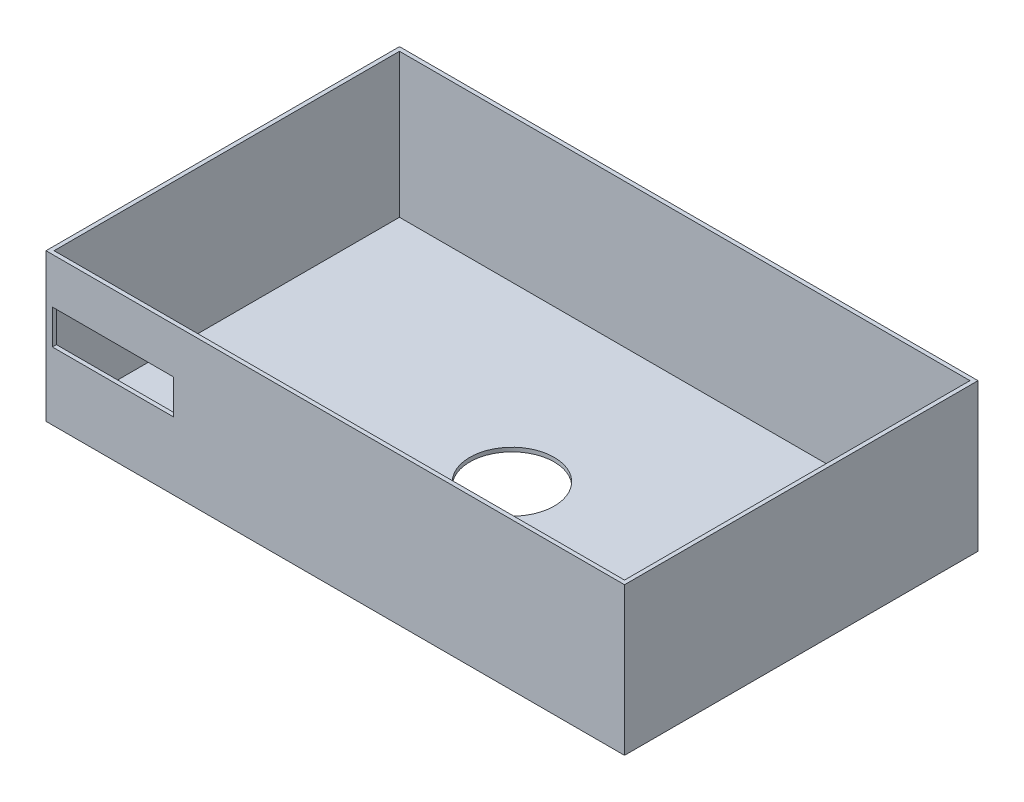
SolidWorks part; units mm, degrees
ref_plane "Front Plane" through (0, 0, 0) normal (0, 0, 1) x (1, 0, 0)
ref_plane "Top Plane" through (0, 0, 0) normal (0, 1, 0) x (1, 0, 0)
ref_plane "Right Plane" through (0, 0, 0) normal (1, 0, 0) x (0, 0, -1)
sketch "Sketch1" plane through (0, 0, 0) normal (0, 1, 0) x (1, 0, 0)
  line L1 (0, 0) -> (1370, 0)
  line L2 (0, 0) -> (0, 837.05)
  line L3 (0, 837.05) -> (1370, 837.05)
  line L4 (1370, 0) -> (1370, 837.05)
  dimension "D1" = 1370
  dimension "D2" = 837.05
extrude "Boss-Extrude1" add sketch "Sketch1" along normal blind 350
shell "Shell1" thickness 9.525
sketch "Sketch3" plane through (0, 0, 0) normal (0, 0, 1) x (1, 0, 0)
  line L1 (15, 242.1) -> (302.4, 242.1)
  line L3 (15, 160.1) -> (302.4, 160.1)
  line L4 (302.4, 242.1) -> (302.4, 160.1)
  line L6 (15, 242.1) -> (15, 160.1)
  line L7 (0, 0) -> (1370, 0) construction
  line L8 (0, 350) -> (0, 0) construction
  dimension "D1" = 82
  dimension "D2" = 160.1
  dimension "D3" = 15
  dimension "D4" = 287.4
extrude "Cut-Extrude1" cut sketch "Sketch3" against normal up to surface (9.525 mm away) up to face at (685, 179.7625, -9.525)
sketch "Sketch7" plane through (0, 0, 0) normal (0, -1, 0) x (1, 0, 0)
  line L0 (685, 0) -> (685, -837.05) construction
  line L1 (0, 0) -> (1370, 0) construction
  line L2 (1370, -837.05) -> (0, -837.05) construction
  circle A0 centre (685, -418.525) radius 100
  dimension "D1" = 200
extrude "Cut-Extrude2" cut sketch "Sketch7" against normal up to next
equation "\"No. Of Teeth\"= 25"
equation "\"Module\"= 1.5"
equation "\"Bore Diameter\"= 10"
equation "\"Pressure Angle\"= 20"
equation "\"Outer Diameter\"= ( \"No. Of Teeth\" + 2 ) * ( \"Module\" )"
equation "\"Pitch diameter\"= \"No. Of Teeth\" * \"Module\""
equation "\"Backlash\"= 0.3 * \"Module\""
equation "\"Arc Length\"= ( ( \"Module\" * pi ) / 2 ) + \"Backlash\""
equation "\"Fillet Radius\"= 0.38 * \"Module\""
equation "\"Tooth Depth\"= IIF ( \"Module\" <= 1.25 , \"Module\" * 2.4 , \"Module\" * 2.25 )"
